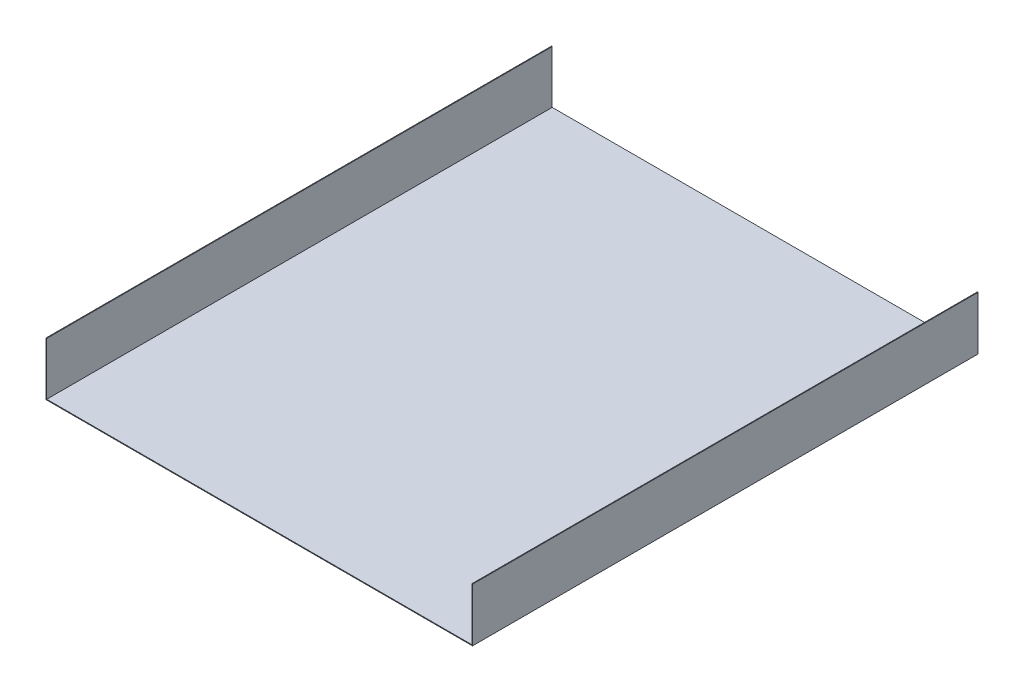
SolidWorks part; units mm, degrees
ref_plane "Front Plane" through (0, 0, 0) normal (0, 0, 1) x (1, 0, 0)
ref_plane "Top Plane" through (0, 0, 0) normal (0, 1, 0) x (1, 0, 0)
ref_plane "Right Plane" through (0, 0, 0) normal (1, 0, 0) x (0, 0, -1)
other "Configuration Table"
sketch "Sketch1" plane through (0, 0, 0) normal (0, 0, 1) x (1, 0, 0)
  line L0 (13.7, 82) -> (13.7, 8)
  line L1 (13.7, 8) -> (604.3, 8)
  line L2 (604.3, 8) -> (604.3, 82)
  line L3 (604.3, 82) -> (603.3, 82)
  line L4 (603.3, 82) -> (603.3, 9)
  line L5 (603.3, 9) -> (14.7, 9)
  line L6 (14.7, 9) -> (14.7, 82)
  line L7 (14.7, 82) -> (13.7, 82)
extrude "CEK_donmus_kutu_U_1.0_1" add sketch "Sketch1" against normal blind 700 separate body
